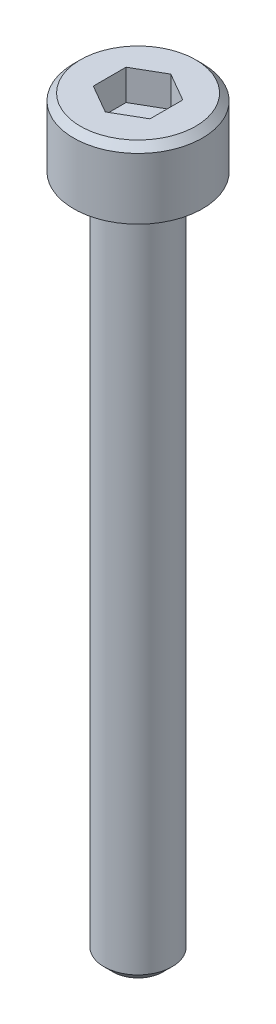
SolidWorks part; units mm, degrees
ref_plane "Front Plane" through (0, 0, 0) normal (0, 0, 1) x (1, 0, 0)
ref_plane "Top Plane" through (0, 0, 0) normal (0, 1, 0) x (1, 0, 0)
ref_plane "Right Plane" through (0, 0, 0) normal (1, 0, 0) x (0, 0, -1)
sketch "Sketch1" plane through (0, 0, 0) normal (0, 0, 1) x (1, 0, 0)
  line L0 (0, -30) -> (1.1, -30)
  line L1 (1.1, -30) -> (1.5, -29.6)
  line L2 (1.5, -29.6) -> (1.5, 0)
  line L3 (1.5, 0) -> (2.84, 0)
  line L4 (2.84, 0) -> (2.84, 2.7)
  line L5 (2.84, 2.7) -> (2.54, 3)
  line L6 (2.54, 3) -> (0, 3)
  line L7 (0, 3) -> (0, -30)
  line L8 (0, -10) -> (0, 1000) construction
revolve "Revolve1" add sketch "Sketch1" angle 360 about L8
cosmetic thread "Cosmetic Thread1"
ref_plane "Plane1" through (0, 3, 0) normal (0, 1, 0) x (1, 0, 0)
sketch "Sketch2" plane through (0, 3, 0) normal (0, 1, 0) x (1, 0, 0)
  line L0 (1.25, -0.7217) -> (0, -1.4434)
  line L1 (0, -1.4434) -> (-1.25, -0.7217)
  line L2 (-1.25, -0.7217) -> (-1.25, 0.7217)
  line L3 (-1.25, 0.7217) -> (0, 1.4434)
  line L4 (0, 1.4434) -> (1.25, 0.7217)
  line L5 (1.25, 0.7217) -> (1.25, -0.7217)
extrude "Cut-Extrude1" cut sketch "Sketch2" against normal blind 1.35
